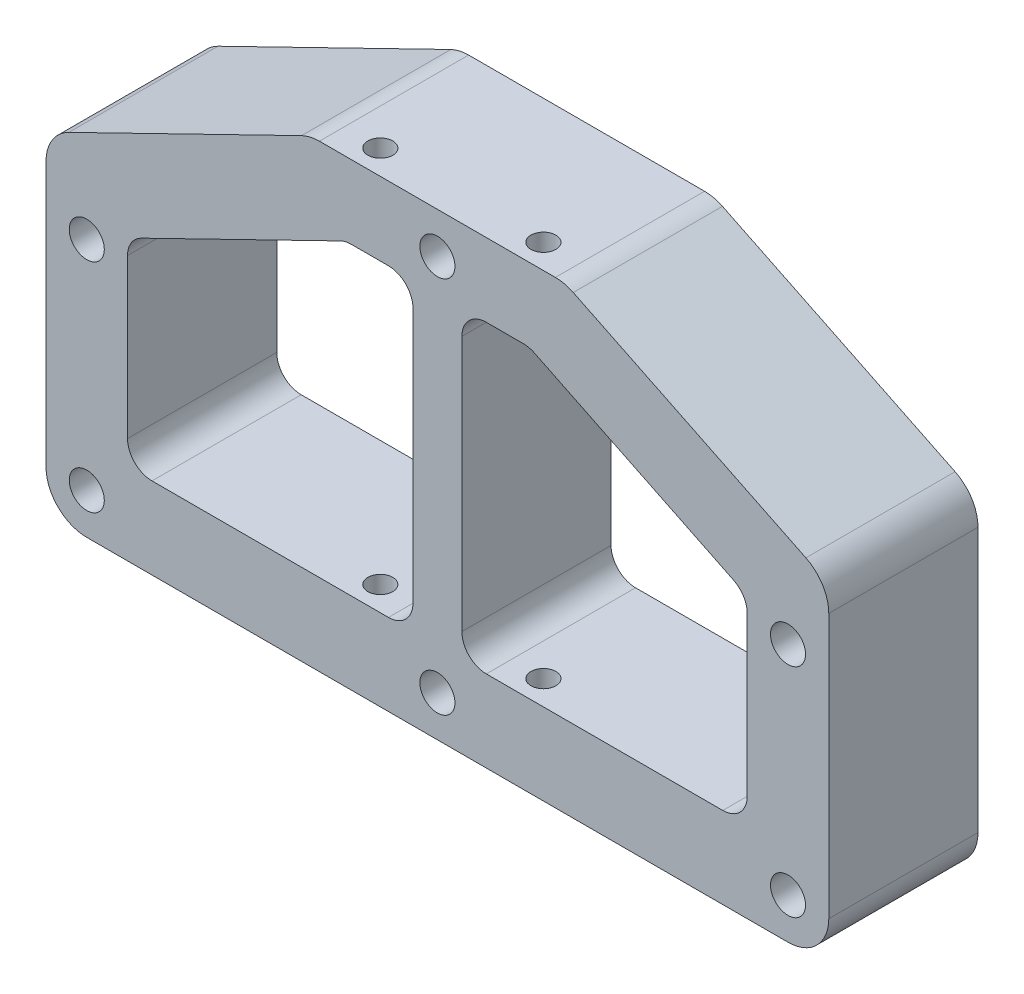
SolidWorks part; units mm, degrees
material "ABS"
ref_plane "前视基准面" through (0, 0, 0) normal (0, 0, 1) x (1, 0, 0)
ref_plane "上视基准面" through (0, 0, 0) normal (0, 1, 0) x (1, 0, 0)
ref_plane "右视基准面" through (0, 0, 0) normal (1, 0, 0) x (0, 0, -1)
other "Configuration Table"
sketch "草图1" plane through (0, 0, 0) normal (0, 0, 1) x (1, 0, 0)
  line L0 (0, 0) -> (0, 104) construction
  line L1 (-8.2819, 111.2395) -> (-56, 56.65)
  line L6 (-56, 0) -> (56, 0)
  line L7 (-56, 0) -> (-56, 56.65)
  line L9 (56, 0) -> (56, 56.65)
  line L10 (-56, 0) -> (56, 56.65) construction
  line L11 (-56, 56.65) -> (56, 0) construction
  line L12 (8.2819, 111.2395) -> (56, 56.65)
  circle A0 centre (0, 0) radius 28.325 construction
  circle A1 centre (0, 104) radius 6
  arc A2 (8.2819, 111.2395) -> (-8.2819, 111.2395) centre (0, 104) ccw
  point P3 (0, 28.325)
  dimension "D4" = 12
  dimension "D5" = 22
  dimension "D1" = 104
  dimension "D2" = 56.65
  dimension "D3" = 112
  dimension "D6" = 56.65
extrude "凸台-拉伸1" add sketch "草图1" along normal blind 18.3
sketch "草图2" plane through (0, 0, 18.3) normal (0, 0, 1) x (1, 0, 0)
  line L0 (15.6226, 56.3463) -> (54.3153, 37.4718) construction
  line L1 (-54.3153, 37.4718) -> (-15.6226, 56.3463) construction
  line L3 (15.6226, 56.3463) -> (56, 36.65)
  line L4 (-56, 36.65) -> (-15.6226, 56.3463)
  line L5 (15.6226, 56.3463) -> (-15.6226, 56.3463)
  line L6 (56, 36.65) -> (56, 56.65)
  line L7 (56, 56.65) -> (30, 116.3463)
  line L8 (30, 116.3463) -> (-30, 116.3463)
  line L9 (-30, 116.3463) -> (-56, 56.65)
  line L10 (-56, 56.65) -> (-56, 36.65)
  line L11 (0, 116.3463) -> (0, 0) construction
  dimension "D1" = 60
  dimension "D2" = 60
extrude "切除-拉伸1" cut sketch "草图2" against normal blind 38
sketch "草图3" plane through (0, 0, 18.3) normal (0, 0, 1) x (1, 0, 0)
  line L0 (-56, 0) -> (56, 0) construction
  line L1 (-43, 5) -> (43, 5) construction
  line L2 (-43, 5) -> (-43, 31.65) construction
  line L3 (-43, 31.65) -> (43, 31.65) construction
  line L4 (43, 5) -> (43, 31.65) construction
  line L5 (-43, 5) -> (43, 31.65) construction
  line L6 (-43, 31.65) -> (43, 5) construction
  line L7 (56, 0) -> (56, 36.65) construction
  line L8 (0, 18.325) -> (0, 0) construction
  line L9 (0, 56.3463) -> (0, 51.3463) construction
  line L10 (-15.6226, 56.3463) -> (15.6226, 56.3463) construction
  circle A4 centre (0, 51.3463) radius 2.15
  circle A5 centre (43, 31.65) radius 2.15
  circle A6 centre (43, 5) radius 2.15
  circle A7 centre (-43, 5) radius 2.15
  circle A8 centre (-43, 31.65) radius 2.15
  circle A9 centre (0, 5) radius 2.15
  point P0 (0, 18.325)
  dimension "D4" = 4.3
  dimension "D5" = 5
  dimension "D1" = 5
  dimension "D2" = 13
  dimension "D3" = 5
extrude "切除-拉伸2" cut sketch "草图3" against normal blind 74
sketch "草图4" [suppressed] plane through (0, 0, 8) normal (0, 0, 1) x (1, 0, 0)
  line L0 (48, 0) -> (48, 65.802)
  line L1 (-56, 0) -> (56, 0) construction
  line L2 (56, 56.65) -> (8.2819, 111.2395) construction
  line L3 (56, 0) -> (56, 56.65) construction
  dimension "D1" = 8
extrude "切除-拉伸-薄壁1" [suppressed] cut sketch "草图4" against normal blind 74 and the other way through all thin
mirror "镜向1" [suppressed] about plane through (0, 0, 0) normal (1, 0, 0)
sketch "草图5" plane through (0, 0, 18.3) normal (0, 0, 1) x (1, 0, 0)
  line L0 (48, 40.5524) -> (48, 0)
  line L1 (15.6226, 56.3463) -> (56, 36.65) construction
  line L2 (-56, 0) -> (56, 0) construction
  line L3 (56, 0) -> (56, 36.65) construction
  dimension "D1" = 8
extrude "切除-拉伸-薄壁3" cut sketch "草图5" against normal blind 74 and the other way through all thin thin type one direction reverse wall 10
mirror "镜向2" about plane through (0, 0, 0) normal (1, 0, 0) of "切除-拉伸-薄壁3"
sketch "草图6" [suppressed] plane through (0, 0, 0) normal (0, 0, -1) x (-1, 0, 0)
  circle A0 centre (0, 51.65) radius 2.15 construction
  circle A1 centre (43, 31.65) radius 2.15 construction
  circle A2 centre (43, 5) radius 2.15 construction
  circle A3 centre (0, 5) radius 2.15 construction
  circle A4 centre (-43, 5) radius 2.15 construction
  circle A5 centre (-43, 31.65) radius 2.15 construction
  circle A6 centre (0, 51.65) radius 2.15 construction
  circle A7 centre (43, 31.65) radius 2.15 construction
  circle A8 centre (43, 5) radius 2.15 construction
  circle A9 centre (0, 5) radius 2.15 construction
  circle A10 centre (-43, 5) radius 2.15 construction
  circle A11 centre (-43, 31.65) radius 2.15 construction
  circle A12 centre (-43, 31.65) radius 2.025
  circle A13 centre (0, 51.65) radius 2.025
  circle A14 centre (43, 31.65) radius 2.025
  circle A15 centre (43, 5) radius 2.025
  circle A16 centre (-43, 5) radius 2.025
  circle A17 centre (0, 5) radius 2.025
  dimension "D1" = 4.05
extrude "切除-拉伸3" [suppressed] cut sketch "草图6" against normal blind 74
sketch "草图7" plane through (0, 0, 0) normal (0, 0, -1) x (-1, 0, 0)
  line L0 (-38, 34.3042) -> (-38, 10)
  line L1 (-38, 10) -> (38, 10)
  line L2 (38, 10) -> (38, 34.3042)
  line L3 (38, 34.3042) -> (11.2636, 47.3463)
  line L4 (11.2636, 47.3463) -> (-11.2636, 47.3463)
  line L5 (-11.2636, 47.3463) -> (-38, 34.3042)
  line L6 (-15.6226, 56.3463) -> (-48, 40.5524) construction
  line L7 (48, 40.5524) -> (15.6226, 56.3463) construction
  circle A0 centre (0, 51.3463) radius 2.15 construction
  circle A1 centre (0, 5) radius 2.15 construction
  circle A2 centre (43, 31.65) radius 2.15 construction
  circle A3 centre (-43, 31.65) radius 2.15 construction
  dimension "D1" = 10
  dimension "D2" = 10
  dimension "D3" = 4
  dimension "D4" = 5
  dimension "D5" = 5
  dimension "D6" = 5
extrude "切除-拉伸4" cut sketch "草图7" against normal blind 40
sketch "草图8" plane through (0, 0, 0) normal (0, 0, -1) x (-1, 0, 0)
  line L0 (0, 47.3463) -> (0, 10) construction
  line L1 (11.2636, 47.3463) -> (-11.2636, 47.3463) construction
  line L2 (-38, 10) -> (38, 10) construction
  line L3 (-3, 47.3463) -> (-3, 10)
  line L4 (3, 47.3463) -> (3, 10)
  line L5 (-3, 47.3463) -> (3, 47.3463)
  line L6 (-3, 10) -> (3, 10)
  dimension "D1" = 3
  dimension "D2" = 3
extrude "凸台-拉伸2" add sketch "草图8" against normal up to surface (18.3 mm away) up to face at (0, 30.5502, 18.3)
fillet "圆角2" radius 3 10 edges at (-11.2636, 47.3463, 9.15) (-38, 34.3042, 9.15) (-3, 47.3463, 9.15) (3, 10, 9.15) (38, 10, 9.15) (38, 34.3042, 9.15) (11.2636, 47.3463, 9.15) (3, 47.3463, 9.15) (-38, 10, 9.15) (-3, 10, 9.15)
fillet "圆角3" radius 5 6 edges at (48, 0, 9.15) (48, 40.5524, 9.15) (-48, 40.5524, 9.15) (-48, 0, 9.15) (15.6226, 56.3463, 9.15) (-15.6226, 56.3463, 9.15)
sketch "草图9" [suppressed] plane through (0, 0, 8) normal (0, 0, 1) x (1, 0, 0)
  line L0 (0, 51.65) -> (43, 31.65) construction
  line L1 (43, 31.65) -> (43, 5) construction
  line L2 (43, 5) -> (-43, 5) construction
  line L3 (-43, 5) -> (-43, 31.65) construction
  line L4 (-43, 31.65) -> (0, 51.65) construction
  line L5 (0, 46.1356) -> (38, 28.4612)
  line L6 (38, 28.4612) -> (38, 10)
  line L7 (38, 10) -> (-38, 10)
  line L8 (-38, 10) -> (-38, 28.4612)
  line L9 (-38, 28.4612) -> (0, 46.1356)
  dimension "D1" = 5
extrude "切除-拉伸5" [suppressed] cut sketch "草图9" against normal up to surface (8 mm away)
fillet "圆角4" [suppressed] radius 3
sketch "草图10" [suppressed] plane through (0, 0, 8) normal (0, 0, 1) x (1, 0, 0)
  line L0 (0, 45.827) -> (0, 10) construction
  line L1 (-35, 10) -> (35, 10) construction
  line L2 (-3, 45.827) -> (-3, 10)
  line L3 (3, 45.827) -> (3, 10)
  line L4 (-3, 45.827) -> (3, 45.827)
  line L5 (-3, 10) -> (3, 10)
  arc A0 (1.2652, 45.5472) -> (-1.2652, 45.5472) centre (0, 42.827) ccw construction
  dimension "D1" = 3
  dimension "D2" = 3
extrude "凸台-拉伸3" [suppressed] add sketch "草图10" against normal up to surface (8 mm away)
fillet "圆角5" [suppressed] radius 3
fillet "圆角6" [suppressed] radius 5
sketch "草图11" [suppressed] plane through (0, 0, 0) normal (0, 0, -1) x (-1, 0, 0)
  line L0 (-11.2585, 95.6786) -> (-38, 65.0864)
  line L1 (-38, 65.0864) -> (-38, 41.6957)
  line L2 (-38, 41.6957) -> (-6, 56.5794)
  line L3 (-6, 56.5794) -> (-6, 91.3509)
  line L4 (0, 104) -> (0, 0) construction
  line L5 (-46.7645, 67.2154) -> (-8.2819, 111.2395) construction
  line L6 (-38, 26.5479) -> (-38, 13) construction
  line L7 (-7.2652, 42.7565) -> (-36.2652, 29.2681) construction
  arc A0 (-11.2585, 95.6786) -> (-6, 91.3509) centre (0, 104) ccw
  circle A1 centre (0, 104) radius 6 construction
  dimension "D1" = 8
  dimension "D2" = 6
  dimension "D3" = 12
  dimension "D4" = 8
extrude "切除-拉伸6" [suppressed] cut sketch "草图11" against normal blind 70
mirror "镜向3" [suppressed] about plane through (0, 0, 0) normal (1, 0, 0)
fillet "圆角7" [suppressed] radius 5
sketch "草图12" plane through (0, 10, 0) normal (0, 1, 0) x (1, 0, 0)
  circle A0 centre (-10, -15.3) radius 1.525 construction
  circle A1 centre (10, -15.3) radius 1.525 construction
  circle A2 centre (-10, -15.3) radius 1.525
  circle A3 centre (10, -15.3) radius 1.525
extrude "切除-拉伸7" cut sketch "草图12" against normal blind 40 and the other way blind 80
equation "\"D6@草图7\"=\"D5@草图7\""
